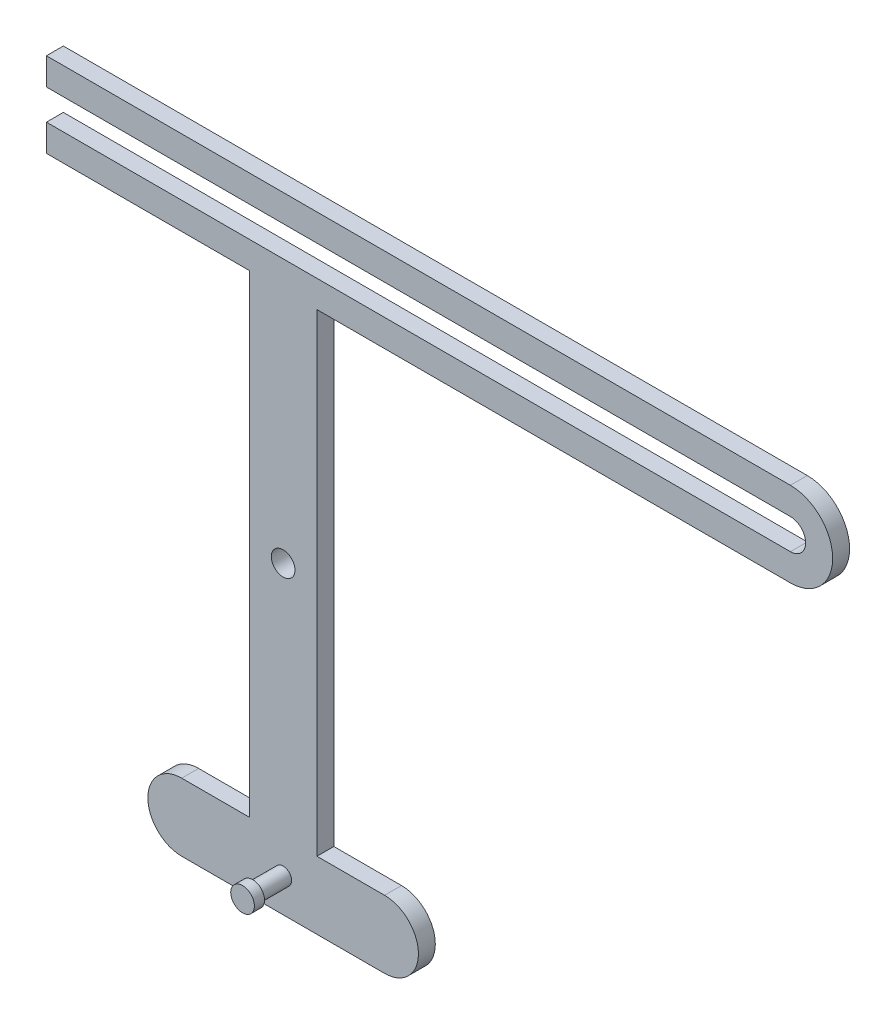
SolidWorks part; units mm, degrees
ref_plane "Front Plane" through (0, 0, 0) normal (0, 0, 1) x (1, 0, 0)
ref_plane "Top Plane" through (0, 0, 0) normal (0, 1, 0) x (1, 0, 0)
ref_plane "Right Plane" through (0, 0, 0) normal (1, 0, 0) x (0, 0, -1)
sketch "Sketch3" plane through (0, 0, 0) normal (0, 0, 1) x (1, 0, 0)
  line L0 (-38.1, 0) -> (38.1, 0) construction
  line L1 (-38.1, 12.7) -> (38.1, 12.7)
  line L2 (-38.1, -12.7) -> (38.1, -12.7)
  arc A0 (-38.1, 12.7) -> (-38.1, -12.7) centre (-38.1, 0) ccw
  arc A1 (38.1, -12.7) -> (38.1, 12.7) centre (38.1, 0) ccw
  point P2 (0, 0)
  dimension "D1" = 76.2
  dimension "D2" = 25.4
extrude "Boss-Extrude1" add sketch "Sketch3" along normal mid plane 6.35
sketch "Sketch4" plane through (0, 0, 0) normal (0, 0, 1) x (1, 0, 0)
  line L0 (38.1, 12.7) -> (-38.1, 12.7) construction
  line L1 (12.7, 12.7) -> (-12.7, 12.7)
  line L2 (12.7, 12.7) -> (12.7, 190.5)
  line L3 (12.7, 190.5) -> (-12.7, 190.5)
  line L4 (-12.7, 12.7) -> (-12.7, 190.5)
  point P6 (0, 12.7)
  dimension "D1" = 25.4
  dimension "D2" = 177.8
extrude "Boss-Extrude2" add sketch "Sketch4" along normal mid plane 6.35
sketch "Sketch5" plane through (0, 0, 0) normal (0, 0, 1) x (1, 0, 0)
  line L0 (-190.5, 206.375) -> (190.5, 206.375) construction
  line L1 (-88.9, 222.25) -> (190.5, 222.25)
  line L2 (-88.9, 190.5) -> (190.5, 190.5)
  line L3 (12.7, 190.5) -> (-12.7, 190.5) construction
  line L4 (-88.9, 222.25) -> (-88.9, 190.5)
  line L5 (-12.7, 190.5) -> (-12.7, 12.7) construction
  arc A1 (190.5, 190.5) -> (190.5, 222.25) centre (190.5, 206.375) ccw
  point P2 (0, 206.375)
  point P9 (0, 206.375)
  dimension "D2" = 381
  dimension "D1" = 31.75
  dimension "D3" = 76.2
extrude "Boss-Extrude3" add sketch "Sketch5" along normal mid plane 6.35
sketch "Sketch6" plane through (0, 0, 3.175) normal (0, 0, 1) x (1, 0, 0)
  line L14 (-88.9, 222.25) -> (-88.9, 190.5) construction
  line L15 (-88.9, 212.09) -> (-88.9, 200.66)
  line L16 (12.7, 200.66) -> (190.5, 200.66)
  line L17 (190.5, 212.09) -> (-88.9, 212.09)
  line L18 (-88.9, 200.66) -> (190.5, 200.66)
  line L19 (190.5, 212.09) -> (-88.9, 212.09)
  arc A7 (190.5, 200.66) -> (190.5, 212.09) centre (190.5, 206.375) ccw
  arc A8 (190.5, 200.66) -> (190.5, 212.09) centre (190.5, 206.375) ccw
  dimension "D1" = 10.16
extrude "Cut-Extrude1" cut sketch "Sketch6" against normal through all
sketch "Sketch7" plane through (0, 0, 3.175) normal (0, 0, 1) x (1, 0, 0)
  line L0 (38.1, 12.7) -> (12.7, 12.7) construction
  circle A0 centre (0, 101.6) radius 4.445
  dimension "D1" = 88.9
  dimension "D2" = 8.89
extrude "Cut-Extrude2" cut sketch "Sketch7" against normal through all contours A0
sketch "Sketch9" plane through (0, 0, 3.175) normal (0, 0, 1) x (1, 0, 0)
  circle A0 centre (0, 0) radius 3.175
  dimension "D1" = 6.35
extrude "Boss-Extrude6" add sketch "Sketch9" along normal blind 15.24
sketch "Sketch10" plane through (0, 0, 18.415) normal (0, 0, 1) x (1, 0, 0)
  circle A0 centre (0, 0) radius 4.445
  dimension "D1" = 8.89
extrude "Boss-Extrude7" add sketch "Sketch10" against normal blind 3.81
